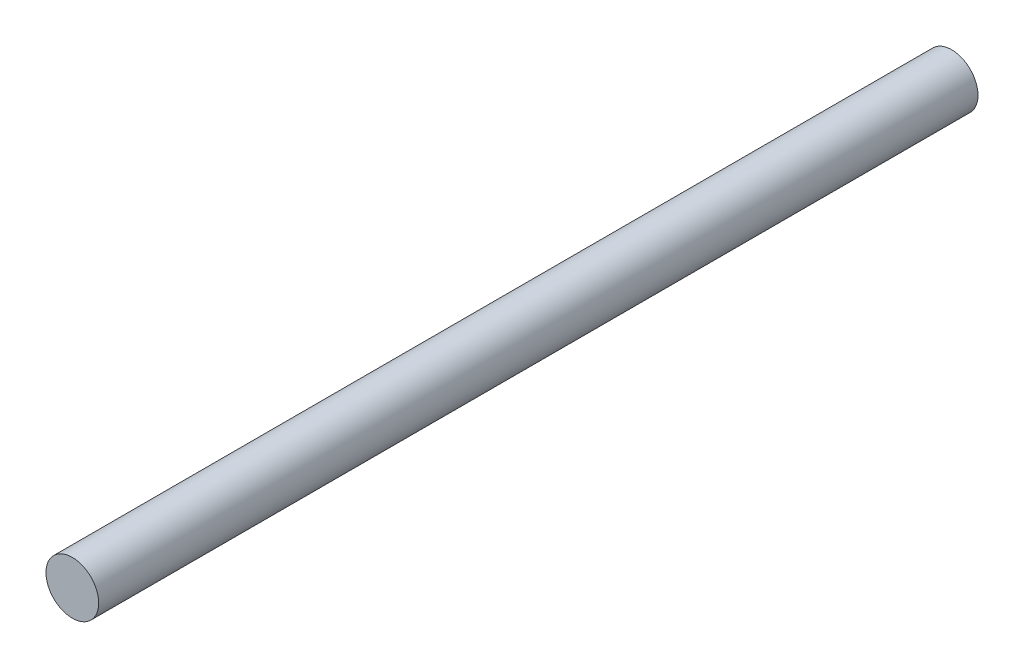
SolidWorks part; units mm, degrees
ref_plane "Front Plane" through (0, 0, 0) normal (1, 0, 0) x (0, 1, 0)
ref_plane "Top Plane" through (0, 0, 0) normal (0, 0, 1) x (0, 1, 0)
ref_plane "Right Plane" through (0, 0, 0) normal (0, 1, 0) x (-1, 0, 0)
sketch "Sketch1" plane through (0, 0, 0) normal (0, 0, 1) x (0, 1, 0)
  circle A0 centre (0, 0) radius 6
  dimension "D1" = 12
extrude "Boss-Extrude1" add sketch "Sketch1" along normal blind 200
